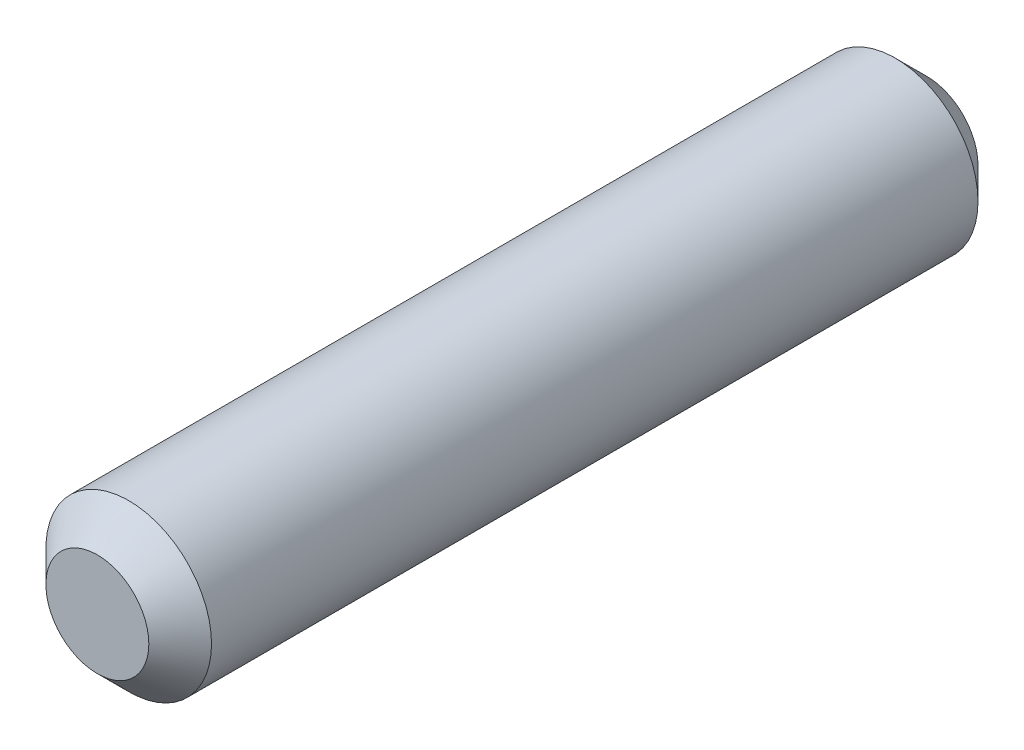
SolidWorks part; units mm, degrees
ref_plane "Front Plane" through (0, 0, 0) normal (0, 0, 1) x (1, 0, 0)
ref_plane "Top Plane" through (0, 0, 0) normal (0, 1, 0) x (1, 0, 0)
ref_plane "Right Plane" through (0, 0, 0) normal (1, 0, 0) x (0, 0, -1)
sketch "Sketch2" plane through (0, 0, 0) normal (0, 0, 1) x (1, 0, 0)
  circle A0 centre (0, 0) radius 1.585
  dimension "D1" = 3.17
extrude "Boss-Extrude2" add sketch "Sketch2" along normal mid plane 15.87
chamfer "Chamfer1" distance 0.6 angle 45 2 edges at (1.585, 0, -7.935) (1.585, 0, 7.935)
